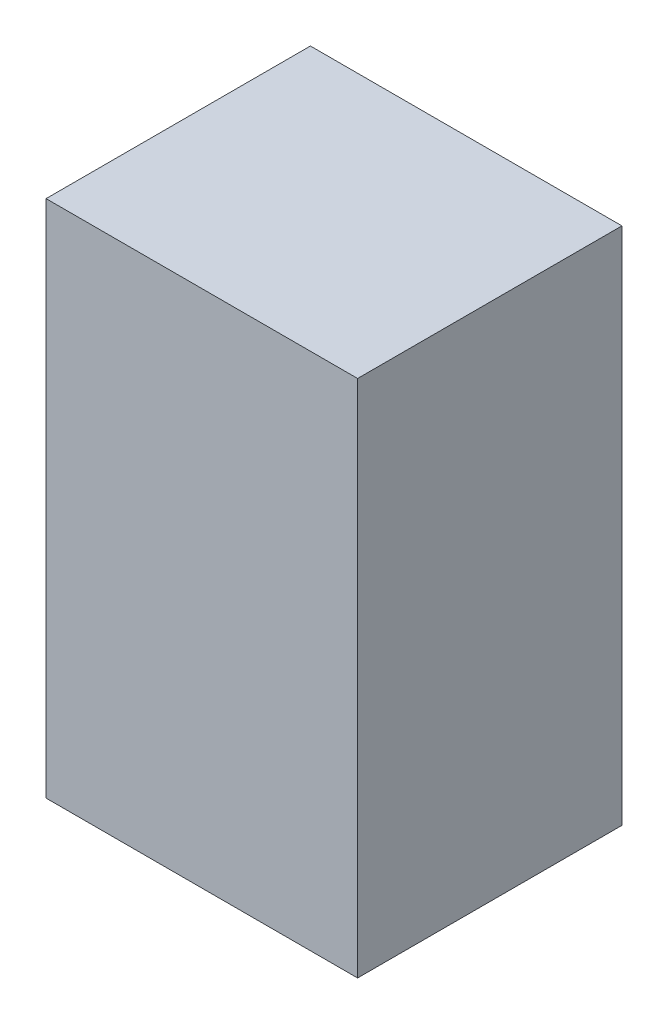
SolidWorks part; units mm, degrees
material "Plain Carbon Steel"
ref_plane "Front Plane" through (0, 0, 0) normal (0, 0, 1) x (1, 0, 0)
ref_plane "Top Plane" through (0, 0, 0) normal (0, 1, 0) x (1, 0, 0)
ref_plane "Right Plane" through (0, 0, 0) normal (1, 0, 0) x (0, 0, -1)
sketch "Sketch1" plane through (0, 0, 0) normal (0, 1, 0) x (1, 0, 0)
  line L1 (-419.1, -355.6) -> (419.1, -355.6)
  line L2 (-419.1, -355.6) -> (-419.1, 355.6)
  line L3 (-419.1, 355.6) -> (419.1, 355.6)
  line L4 (419.1, -355.6) -> (419.1, 355.6)
  line L5 (-419.1, -355.6) -> (419.1, 355.6) construction
  line L6 (-419.1, 355.6) -> (419.1, -355.6) construction
  point P0 (0, 0)
  dimension "D1" = 711.2
  dimension "D2" = 838.2
extrude "Boss-Extrude1" add sketch "Sketch1" along normal blind 1397
